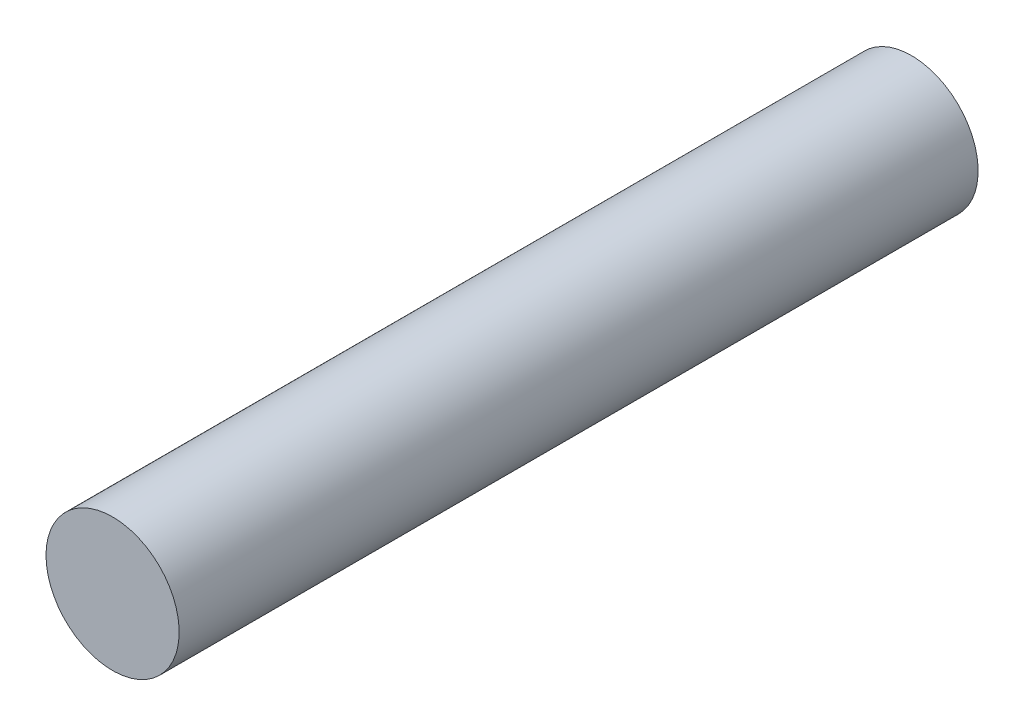
SolidWorks part; units mm, degrees
ref_plane "Front Plane" through (0, 0, 0) normal (0, 0, 1) x (1, 0, 0)
ref_plane "Top Plane" through (0, 0, 0) normal (0, 1, 0) x (1, 0, 0)
ref_plane "Right Plane" through (0, 0, 0) normal (1, 0, 0) x (0, 0, -1)
sketch "Sketch2" plane through (0, 0, 0) normal (0, 0, 1) x (1, 0, 0)
  circle A0 centre (0, 0) radius 6.35
  dimension "D1" = 12.7
extrude "Boss-Extrude1" add sketch "Sketch2" along normal blind 76.2
